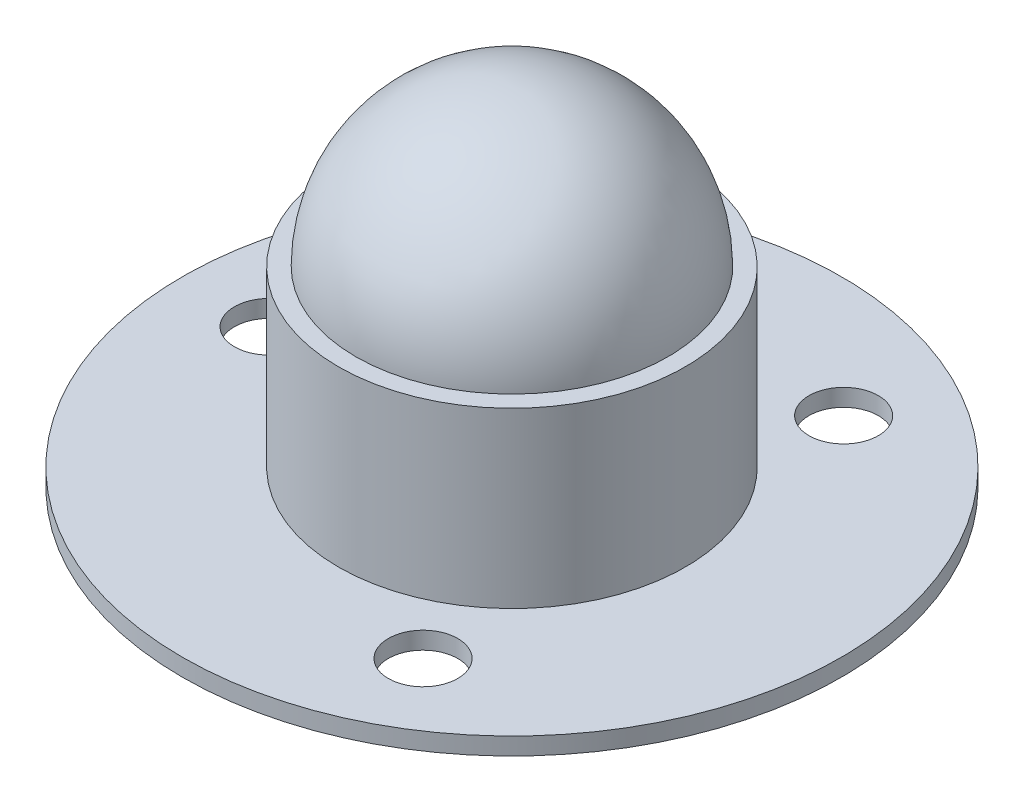
SolidWorks part; units mm, degrees
ref_plane "Front Plane" through (0, 0, 0) normal (0, 0, 1) x (1, 0, 0)
ref_plane "Top Plane" through (0, 0, 0) normal (0, 1, 0) x (1, 0, 0)
ref_plane "Right Plane" through (0, 0, 0) normal (1, 0, 0) x (0, 0, -1)
sketch "Sketch1" plane through (0, 0, 0) normal (0, 1, 0) x (1, 0, 0)
  line L0 (-19, 0) -> (-14, 0)
  circle A0 centre (0, 0) radius 19
  circle A1 centre (-14, 0) radius 2
  circle A2 centre (7, 12.1244) radius 2
  circle A3 centre (7, -12.1244) radius 2
  point P6 (0, 0)
  point P7 (-10.5822, 0)
  dimension "D1" = 3
extrude "Boss-Extrude1" add sketch "Sketch1" along normal mid plane 1
sketch "Sketch2" plane through (0, 0.5, 0) normal (0, 1, 0) x (1, 0, 0)
  circle A0 centre (0, 0) radius 10
extrude "Boss-Extrude2" add sketch "Sketch2" along normal blind 10
sketch "Sketch3" plane through (0, 10.5, 0) normal (0, 1, 0) x (1, 0, 0)
  line L0 (0, 9) -> (0, -9)
  circle A0 centre (0, 0) radius 9
revolve "Revolve1" add sketch "Sketch3" angle 360 about L0
